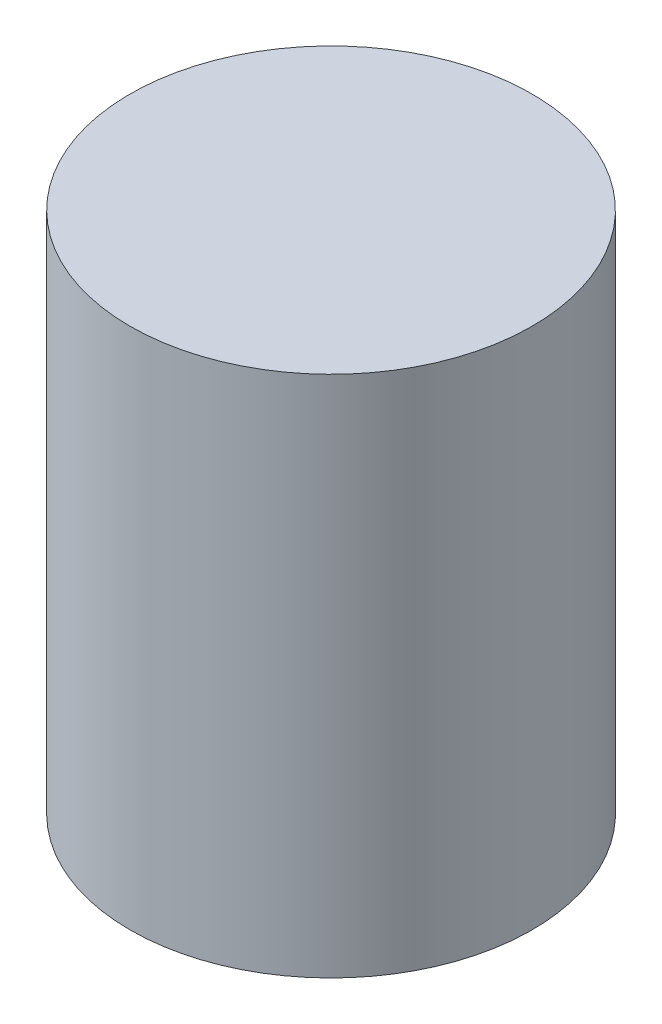
SolidWorks part; units mm, degrees
ref_plane "前视基准面" through (0, 0, 0) normal (0, 0, 1) x (1, 0, 0)
ref_plane "上视基准面" through (0, 0, 0) normal (0, 1, 0) x (1, 0, 0)
ref_plane "右视基准面" through (0, 0, 0) normal (1, 0, 0) x (0, 0, -1)
sketch "草图1" plane through (0, 0, 0) normal (0, 1, 0) x (1, 0, 0)
  circle A0 centre (-30.1074, 28.4139) radius 4.5
extrude "凸台-拉伸1" add sketch "草图1" along normal blind 11.7
